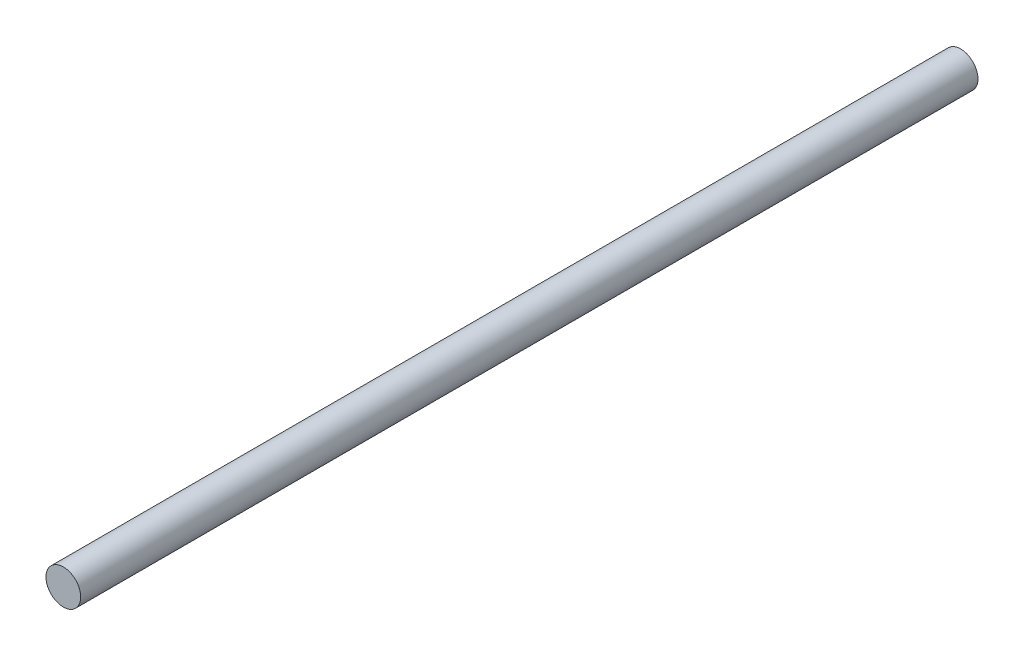
SolidWorks part; units mm, degrees
material "Сталь 20пс ГОСТ 535-88"
ref_plane "Спереди" through (0, 0, 0) normal (0, 0, 1) x (1, 0, 0)
ref_plane "Сверху" through (0, 0, 0) normal (0, 1, 0) x (1, 0, 0)
ref_plane "Справа" through (0, 0, 0) normal (1, 0, 0) x (0, 0, -1)
other "Configuration Table"
sketch "Эскиз1" plane through (0, 0, 0) normal (0, 0, 1) x (1, 0, 0)
  circle A0 centre (0, 0) radius 3
  dimension "D1" = 6
extrude "Бобышка-Вытянуть1" add sketch "Эскиз1" along normal blind 155
